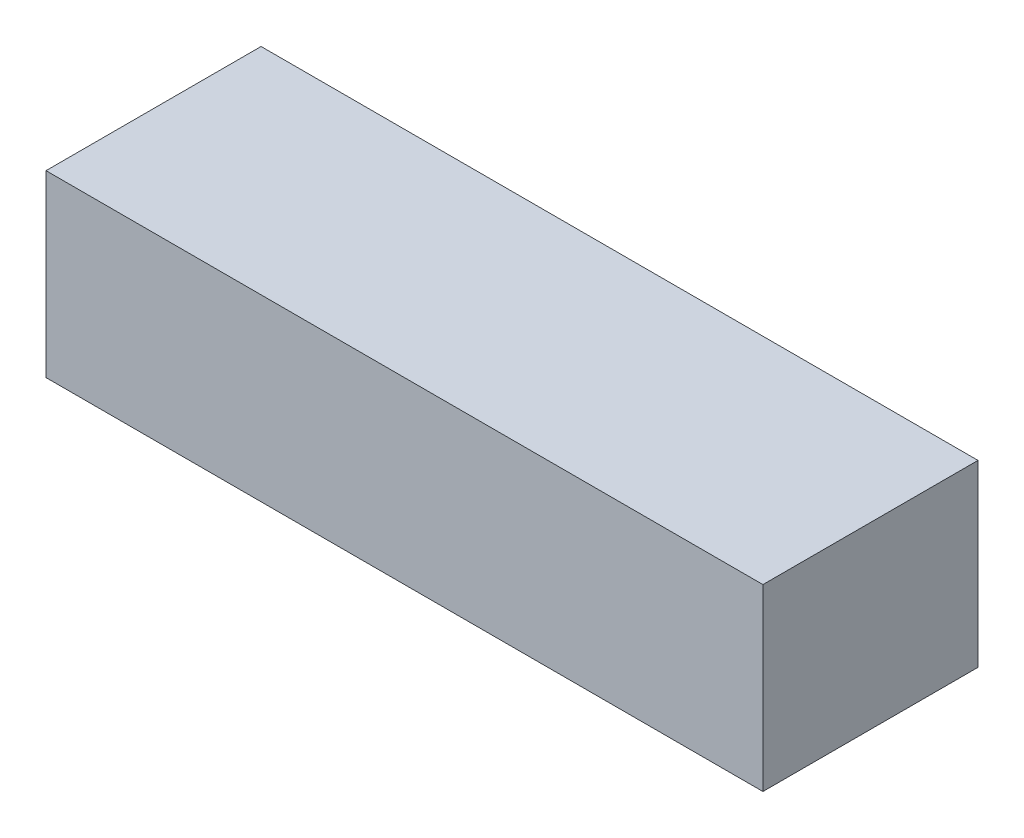
SolidWorks part; units mm, degrees
ref_plane "前视基准面" through (0, 0, 0) normal (0, 0, 1) x (1, 0, 0)
ref_plane "上视基准面" through (0, 0, 0) normal (0, 1, 0) x (1, 0, 0)
ref_plane "右视基准面" through (0, 0, 0) normal (1, 0, 0) x (0, 0, -1)
other "Configuration Table"
sketch "草图1" plane through (0, 0, 0) normal (0, 1, 0) x (1, 0, 0)
  line L0 (7.7745, 0) -> (27.7745, 0)
  line L1 (27.7745, 0) -> (27.7745, 6)
  line L2 (27.7745, 6) -> (7.7745, 6)
  line L3 (7.7745, 6) -> (7.7745, 0)
extrude "凸台-拉伸1" add sketch "草图1" along normal blind 5
